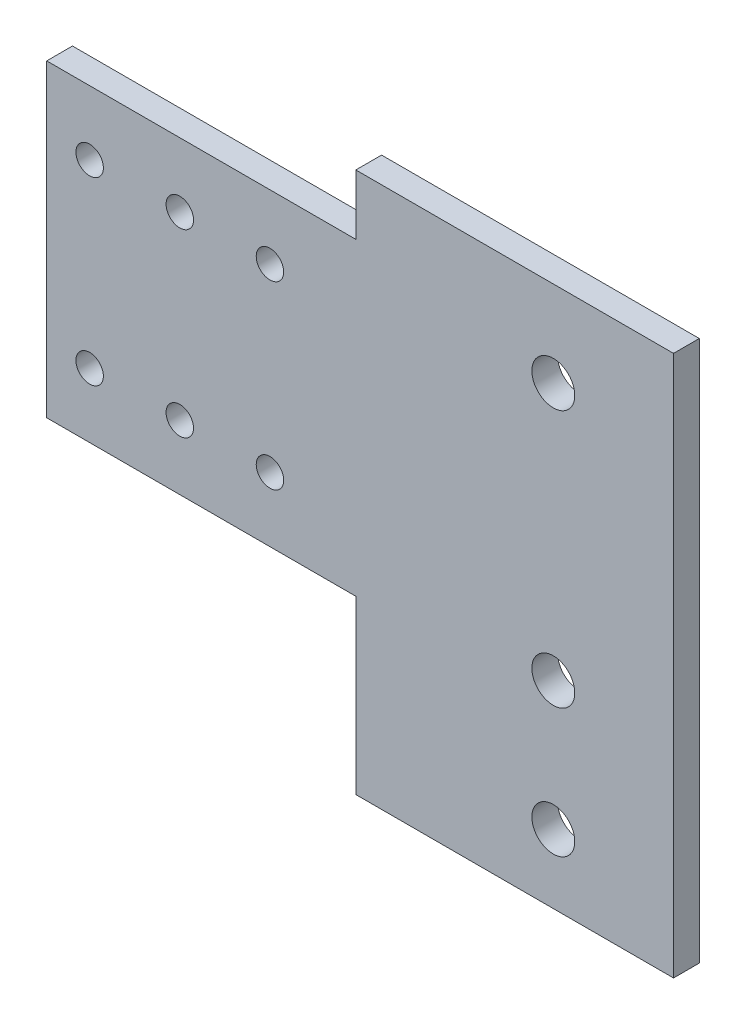
SolidWorks part; units mm, degrees
material "Thornel VCB-20 碳布"
ref_plane "前视基准面" through (0, 0, 0) normal (0, 0, 1) x (1, 0, 0)
ref_plane "上视基准面" through (0, 0, 0) normal (0, 1, 0) x (1, 0, 0)
ref_plane "右视基准面" through (0, 0, 0) normal (1, 0, 0) x (0, 0, -1)
other "Configuration Table"
sketch "草图1" plane through (0, 0, 0) normal (0, 0, 1) x (1, 0, 0)
  line L0 (0, 0) -> (36, 0)
  line L1 (36, 0) -> (36, 20)
  line L2 (36, 20) -> (73, 20)
  line L3 (73, 20) -> (73, -56)
  line L4 (73, -56) -> (36, -56)
  line L5 (36, -56) -> (36, -36)
  line L6 (36, -36) -> (0, -36)
  line L7 (0, -36) -> (0, 0)
  dimension "D1" = 36
  dimension "D2" = 36
  dimension "D3" = 20
  dimension "D4" = 37
extrude "凸台-拉伸1" add sketch "草图1" along normal blind 3
sketch "草图2" plane through (0, 0, 0) normal (0, 0, -1) x (-1, 0, 0)
  line L0 (-36, 0) -> (0, 0) construction
  line L1 (-26, -7.5) -> (-5, -7.5) construction
  line L2 (-26, -7.5) -> (-26, -28.5) construction
  line L3 (-26, -28.5) -> (-5, -28.5) construction
  line L4 (-5, -7.5) -> (-5, -28.5) construction
  line L5 (0, -36) -> (-36, -36) construction
  line L6 (0, 0) -> (0, -36) construction
  line L7 (-36, -36) -> (-36, -56) construction
  circle A0 centre (-26, -7.5) radius 1.6
  circle A1 centre (-26, -28.5) radius 1.6
  circle A2 centre (-5, -7.5) radius 1.6
  circle A3 centre (-5, -28.5) radius 1.6
  circle A4 centre (-15.5, -28.5) radius 1.6
  circle A5 centre (-15.5, -7.5) radius 1.6
  dimension "D5" = 3.2
  dimension "D1" = 7.5
  dimension "D2" = 7.5
  dimension "D3" = 5
  dimension "D4" = 10
extrude "切除-拉伸1" cut sketch "草图2" against normal through all
sketch "草图3" plane through (0, 0, 0) normal (0, 0, -1) x (-1, 0, 0)
  circle A1 centre (-59, -33) radius 2.5
  circle A2 centre (-59, -33) radius 2.5
  circle A3 centre (-59, -48) radius 2.5
  circle A4 centre (-59, -48) radius 2.5
  dimension "D1" = 0
  dimension "D2" = 0
extrude "切除-拉伸2" cut sketch "草图3" against normal through all
sketch "草图4" plane through (0, 0, 0) normal (0, 0, -1) x (-1, 0, 0)
  circle A0 centre (-59, -3) radius 2.5 construction
  circle A1 centre (-59, -3) radius 2.5
  circle A2 centre (-59, 12) radius 2.5 construction
  circle A3 centre (-59, 12) radius 2.5
extrude "切除-拉伸3" cut sketch "草图4" against normal through all
sketch "草图5" plane through (0, 0, 3) normal (0, 0, 1) x (1, 0, 0)
  line L0 (73, 20) -> (36, 20)
  line L1 (36, 20) -> (36, 7)
  line L2 (36, 7) -> (73, 7)
  line L3 (73, 7) -> (73, 20)
  line L8 (0, 0) -> (0, -36)
  line L9 (0, -36) -> (36, -36)
  line L10 (36, -36) -> (36, -56)
  line L11 (36, -56) -> (73, -56)
  line L12 (73, -56) -> (73, 20)
  line L13 (73, 20) -> (36, 20)
  line L14 (36, 20) -> (36, 0)
  line L15 (36, 0) -> (0, 0)
  line L16 (0, 0) -> (0, -36) construction
  line L17 (0, -36) -> (36, -36) construction
  line L18 (36, -36) -> (36, -56) construction
  line L19 (36, -56) -> (73, -56) construction
  line L20 (73, -56) -> (73, 20) construction
  line L21 (73, 20) -> (36, 20) construction
  line L22 (36, 20) -> (36, 0) construction
  line L23 (36, 0) -> (0, 0) construction
  dimension "D2" = 13
  dimension "D1" = 0
extrude "切除-拉伸4" cut sketch "草图5" against normal through all
